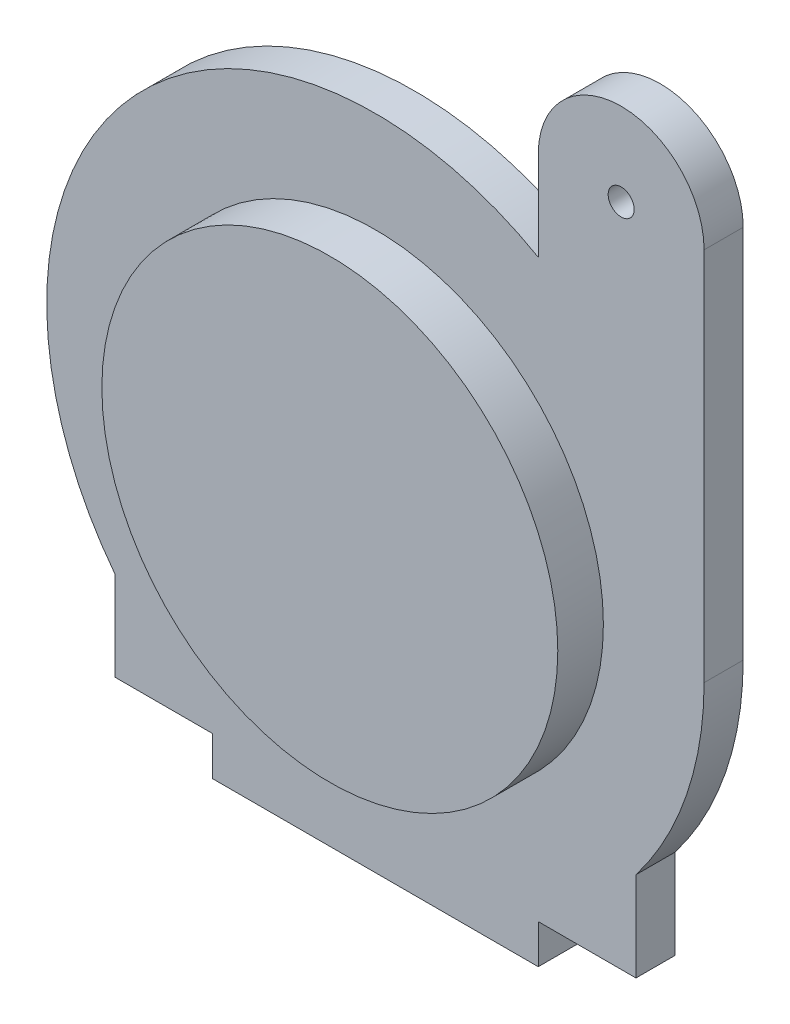
SolidWorks part; units mm, degrees
ref_plane "Front Plane" through (0, 0, 0) normal (0, 0, 1) x (1, 0, 0)
ref_plane "Top Plane" through (0, 0, 0) normal (0, 1, 0) x (1, 0, 0)
ref_plane "Right Plane" through (0, 0, 0) normal (1, 0, 0) x (0, 0, -1)
sketch "Sketch1" plane through (0, 0, 0) normal (0, 0, 1) x (1, 0, 0)
  line L0 (0, 0) -> (7.5, 0)
  line L1 (7.5, 0) -> (7.5, -3)
  line L2 (7.5, -3) -> (32.5, -3)
  line L3 (32.5, -3) -> (32.5, 0)
  line L4 (32.5, 0) -> (40, 0)
  line L8 (7.5, 0) -> (32.5, 0) construction
  line L9 (0, 0) -> (0, 6.8671)
  line L10 (40, 0) -> (40, 6.8671)
  line L11 (45.2315, 22.2499) -> (45.2315, 51.0239)
  line L12 (32.5, 44.1674) -> (32.5, 51.0239)
  circle A2 centre (20, 22.2499) radius 17.2656
  arc A7 (40, 6.8671) -> (45.2315, 22.2499) centre (20, 22.2499) ccw
  arc A8 (32.5, 51.0239) -> (45.2315, 51.0239) centre (38.8658, 51.0239) cw
  circle A9 centre (38.8658, 51.0239) radius 1
  arc A10 (32.5, 44.1674) -> (0, 6.8671) centre (20, 22.2499) ccw
  circle A11 centre (20, 22.2499) radius 10
  point P18 (45.2315, 22.2499)
  point P23 (32.5, 44.1674)
  dimension "D5" = 20
  dimension "D3" = 2
  dimension "D1" = 25
  dimension "D2" = 3
  dimension "D4" = 7.5
extrude "Boss-Extrude5" add sketch "Sketch1" along normal blind 3 contours A2 A11 | L0 L8 L4 L10 A7 L11 A8 L12 A10 L9 A2 A9 | L8 L1 L2 L3
sketch "Sketch2" plane through (0, 0, 0) normal (0, 0, -1) x (-1, 0, 0)
  circle A0 centre (-20, 22.2499) radius 17.5
  dimension "D1" = 35
extrude "Boss-Extrude6" add sketch "Sketch2" against normal blind 6.5
